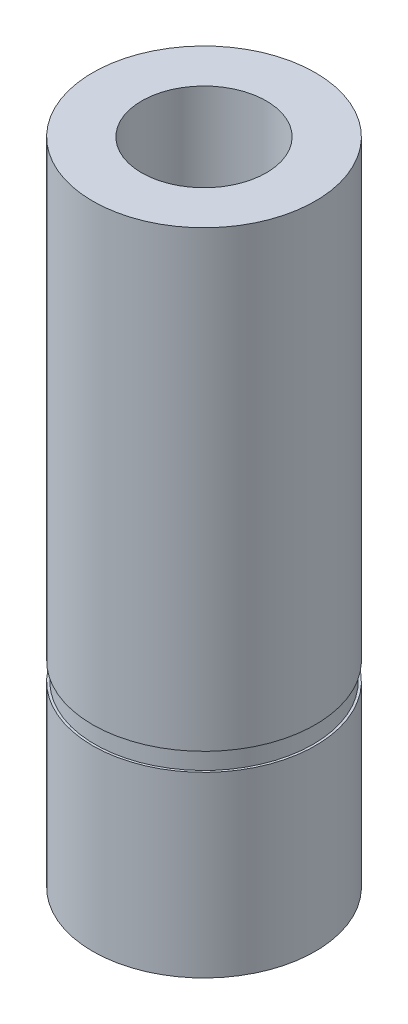
SolidWorks part; units mm, degrees
ref_plane "Front Plane" through (0, 0, 0) normal (0, 0, 1) x (1, 0, 0)
ref_plane "Top Plane" through (0, 0, 0) normal (0, 1, 0) x (1, 0, 0)
ref_plane "Right Plane" through (0, 0, 0) normal (1, 0, 0) x (0, 0, -1)
sketch "Sketch1" plane through (0, 0, 0) normal (0, 1, 0) x (1, 0, 0)
  circle A0 centre (0, 0) radius 6.125
  circle A1 centre (0, 0) radius 3.43
  dimension "D1" = 12.25
extrude "Boss-Extrude1" add sketch "Sketch1" along normal mid plane 35.75
sketch "Sketch2" plane through (0, -17.875, 0) normal (0, -1, 0) x (1, 0, 0)
  circle A0 centre (0, 0) radius 6.25
extrude "Cut-Extrude-Thin1" cut sketch "Sketch2" against normal blind 1 from offset 9.8 thin thin type mid plane wall 0.5 offset against normal yes
